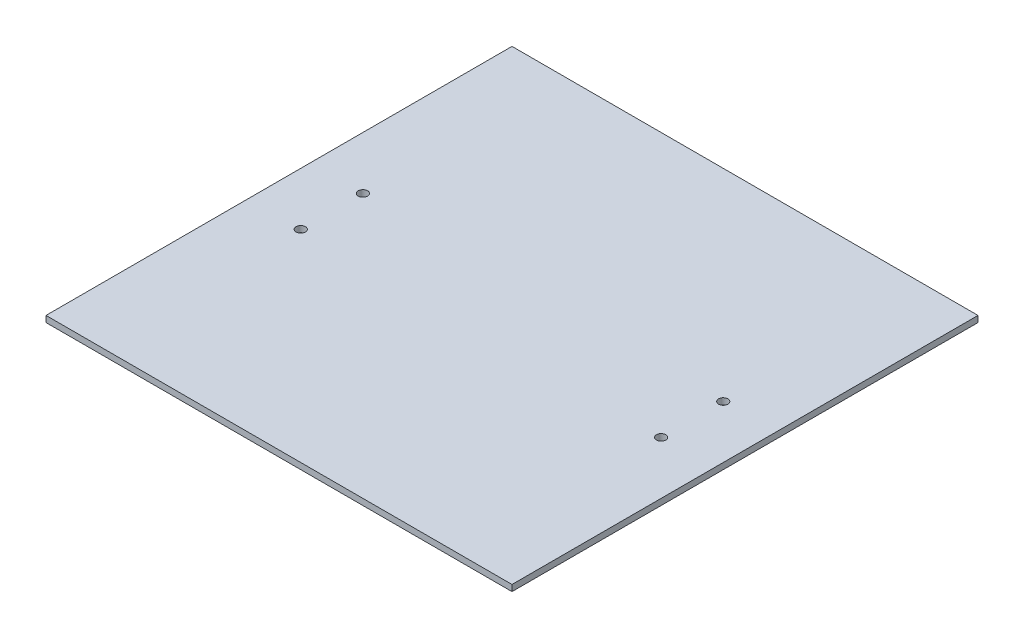
SolidWorks part; units mm, degrees
ref_plane "Front Plane" through (0, 0, 0) normal (0, 0, 1) x (1, 0, 0)
ref_plane "Top Plane" through (0, 0, 0) normal (0, 1, 0) x (1, 0, 0)
ref_plane "Right Plane" through (0, 0, 0) normal (1, 0, 0) x (0, 0, -1)
sketch "Sketch1" plane through (0, 0, 0) normal (0, 1, 0) x (1, 0, 0)
  line L1 (0, 0) -> (150, 0)
  line L2 (0, 0) -> (0, 150)
  line L3 (0, 150) -> (150, 150)
  line L4 (150, 0) -> (150, 150)
  line L5 (17, 85) -> (133, 85)
  line L6 (17, 85) -> (17, 65)
  line L7 (17, 65) -> (133, 65)
  line L8 (133, 85) -> (133, 65)
  circle A0 centre (17, 85) radius 1.5
  circle A1 centre (17, 65) radius 1.5
  circle A3 centre (133, 85) radius 1.5
  circle A4 centre (133, 65) radius 1.5
  dimension "D1" = 150
  dimension "D2" = 150
  dimension "D3" = 20
  dimension "D4" = 116
  dimension "D5" = 65
  dimension "D6" = 17
  dimension "D7" = 17
extrude "Boss-Extrude1" add sketch "Sketch1" along normal blind 2 contours L1 L4 L3 L2 A4 L7 A1 L6 A0 L5 A3 L8 | A4 L8 A3 L5 A0 L6 A1 L7
